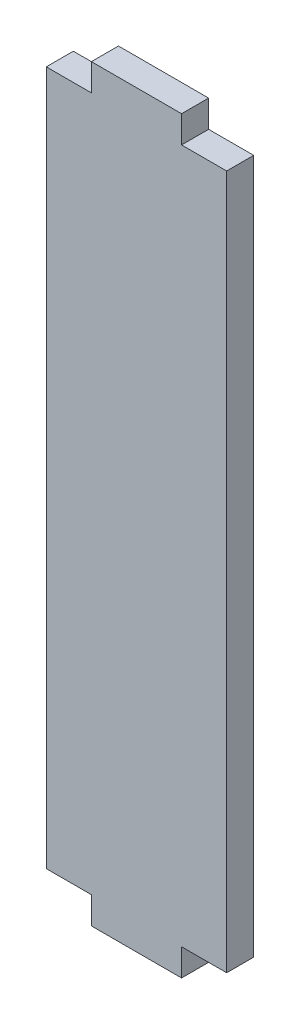
SolidWorks part; units mm, degrees
ref_plane "Front Plane" through (0, 0, 0) normal (0, 0, 1) x (1, 0, 0)
ref_plane "Top Plane" through (0, 0, 0) normal (0, 1, 0) x (1, 0, 0)
ref_plane "Right Plane" through (0, 0, 0) normal (1, 0, 0) x (0, 0, -1)
sketch "Sketch2" plane through (0, 0, 0) normal (0, 0, 1) x (1, 0, 0)
  line L0 (5, 38.5) -> (5, 41.5)
  line L1 (-10, 38.5) -> (-5, 38.5)
  line L2 (-10, 38.5) -> (-10, -38.5)
  line L3 (-10, -38.5) -> (-5, -38.5)
  line L4 (10, 38.5) -> (10, -38.5)
  line L5 (-10, 38.5) -> (10, -38.5) construction
  line L6 (-10, -38.5) -> (10, 38.5) construction
  line L7 (5, 41.5) -> (-5, 41.5)
  line L8 (-5, 41.5) -> (-5, 38.5)
  line L9 (5, 38.5) -> (10, 38.5)
  line L10 (-5, -38.5) -> (-5, -41.5)
  line L11 (-5, -41.5) -> (5, -41.5)
  line L12 (5, -41.5) -> (5, -38.5)
  line L13 (5, -38.5) -> (10, -38.5)
  point P0 (0, 0)
  point P9 (-5, 40)
  dimension "D1" = 77
  dimension "D2" = 20
  dimension "D3" = 10
  dimension "D4" = 3
  dimension "D5" = 5
  dimension "D6" = 3
  dimension "D7" = 5
extrude "Boss-Extrude1" add sketch "Sketch2" along normal blind 3
